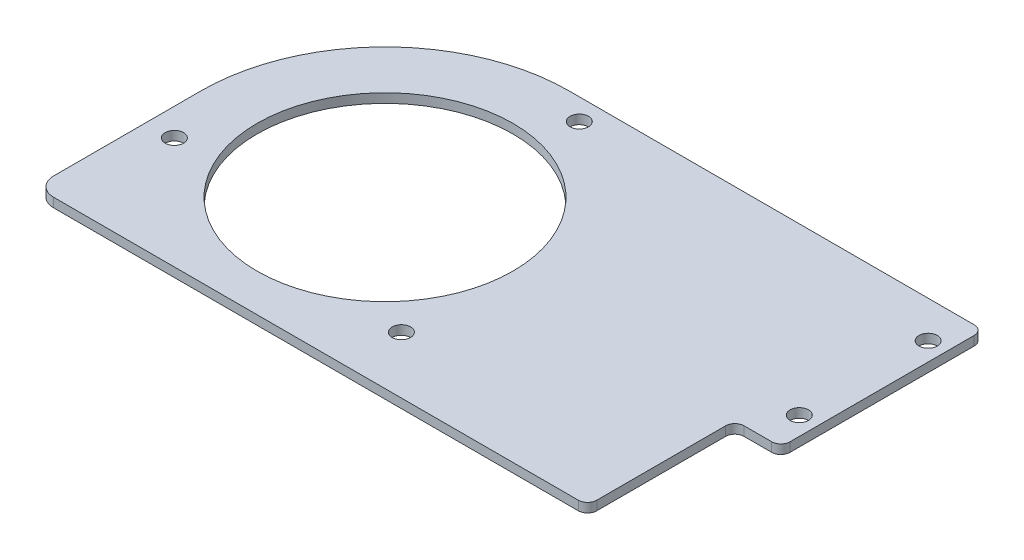
SolidWorks part; units mm, degrees
ref_plane "Front Plane" through (0, 0, 0) normal (0, 0, 1) x (1, 0, 0)
ref_plane "Top Plane" through (0, 0, 0) normal (0, 1, 0) x (1, 0, 0)
ref_plane "Right Plane" through (0, 0, 0) normal (1, 0, 0) x (0, 0, -1)
sketch "Sketch1" plane through (0, 0, 0) normal (0, 1, 0) x (1, 0, 0)
  line L0 (0, 114.3) -> (0, -101.6) construction
  line L1 (279.4, 127) -> (0, 127)
  line L2 (285.75, 120.65) -> (285.75, -6.35)
  line L3 (247.65, -114.3) -> (-114.3, -114.3)
  line L4 (-127, 0) -> (-127, -101.6)
  line L5 (260.35, -12.7) -> (279.4, -12.7)
  line L6 (273.05, -12.7) -> (273.05, 127) construction
  line L7 (-127, 0) -> (285.75, 0) construction
  line L8 (0, 0) -> (-127, -43.7296) construction
  line L11 (254, -107.95) -> (254, -19.05)
  circle A0 centre (0, 0) radius 88.265
  circle A1 centre (0, 0) radius 114.3 construction
  circle A2 centre (-108.0728, -37.2124) radius 6.35
  arc A3 (260.35, -12.7) -> (254, -19.05) centre (260.35, -19.05) ccw
  arc A4 (-127, 0) -> (0, 127) centre (0, 0) cw
  circle A5 centre (21.8095, 112.2) radius 6.35
  circle A6 centre (86.2633, -74.9875) radius 6.35
  arc A7 (-114.3, -114.3) -> (-127, -101.6) centre (-114.3, -101.6) cw
  arc A8 (247.65, -114.3) -> (254, -107.95) centre (247.65, -107.95) ccw
  arc A9 (285.75, -6.35) -> (279.4, -12.7) centre (279.4, -6.35) cw
  arc A10 (279.4, 127) -> (285.75, 120.65) centre (279.4, 120.65) cw
  circle A11 centre (273.05, 101.6) radius 6.35
  circle A12 centre (273.05, 12.7) radius 6.35
  point P0 (0, 0)
  point P11 (0, 0)
  point P32 (254, -114.3)
  point P46 (0, 0)
  dimension "D3" = 176.53
  dimension "D5" = 228.6
  dimension "D6" = 12.7
  dimension "D7" = 127
  dimension "D8" = 101.6
  dimension "D11" = 31.75
  dimension "D12" = 25.4
  dimension "D14" = 12.7
  dimension "D9" = 6.35
  dimension "D10" = 12.7
  dimension "D1" = 127
  dimension "D2" = 114.3
  dimension "D4" = 19
  dimension "D13" = 12.7
  dimension "D15" = 25.4
  dimension "D16" = 412.75
extrude "Boss-Extrude1" add sketch "Sketch1" along normal blind 6.35
sketch "Sketch3" plane through (0, 6.35, 0) normal (0, 1, 0) x (1, 0, 0)
  line L0 (79.375, 127) -> (79.375, -114.3) construction
  line L5 (382.3904, 6.35) -> (-202.4477, 6.35) construction
  line L6 (339.725, -158.75) -> (-180.975, -158.75)
  line L7 (339.725, -158.75) -> (339.725, 171.45)
  line L8 (339.725, 171.45) -> (-180.975, 171.45)
  line L9 (-180.975, -158.75) -> (-180.975, 171.45)
  line L10 (339.725, -158.75) -> (-180.975, 171.45) construction
  line L11 (339.725, 171.45) -> (-180.975, -158.75) construction
  line L26 (285.75, -6.35) -> (285.75, 120.65) construction
  line L27 (-127, 0) -> (-127, -101.6) construction
  line L28 (-114.3, -114.3) -> (247.65, -114.3) construction
  line L29 (279.4, 127) -> (0, 127) construction
  line L30 (285.75, -6.35) -> (285.75, 120.65)
  line L31 (-127, 0) -> (-127, -101.6)
  line L32 (-114.3, -114.3) -> (247.65, -114.3)
  line L33 (279.4, 127) -> (0, 127)
  point P1 (79.375, 6.35)
  dimension "D1" = 520.7
  dimension "D2" = 206.375
  dimension "D3" = 330.2
  dimension "D4" = 120.65
  dimension "D7" = 412.75
  dimension "D8" = 241.3
